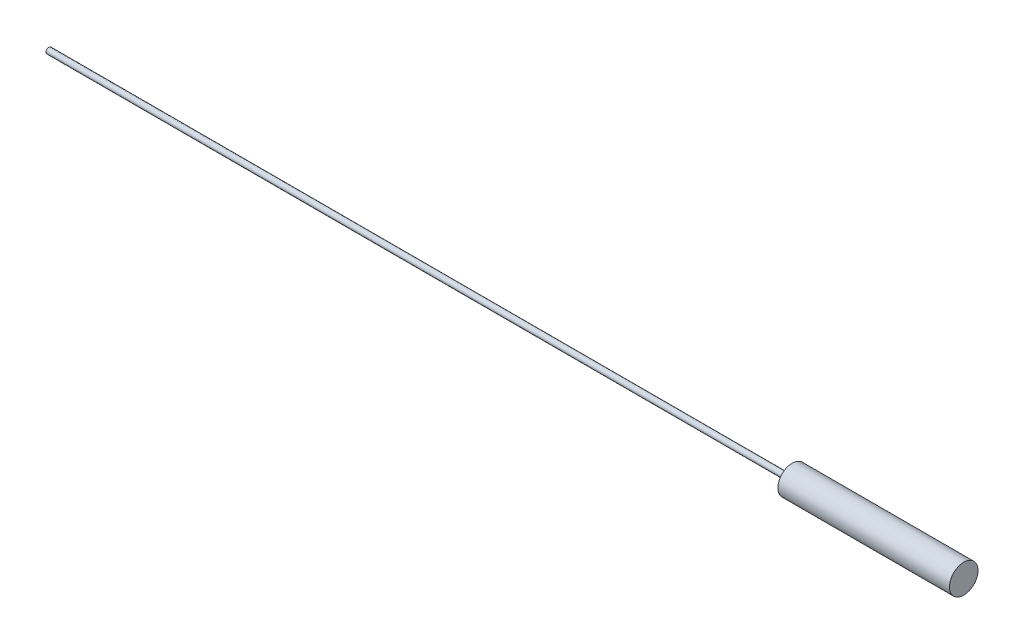
SolidWorks part; units mm, degrees
material "PVC 0.007 Plasticized"
ref_plane "Front" through (0, 0, 0) normal (0, 0, 1) x (1, 0, 0)
ref_plane "Top" through (0, 0, 0) normal (0, 1, 0) x (1, 0, 0)
ref_plane "Right" through (0, 0, 0) normal (1, 0, 0) x (0, 0, -1)
sketch "Sketch1" plane through (0, 0, 0) normal (0, 1, 0) x (1, 0, 0)
  line L0 (-60, 3.4256) -> (60, 3.4256)
  line L2 (-60, 3.4256) -> (60, 3.4256)
  line L3 (-60, 3.4256) -> (-60, -6.5744)
  line L4 (-60, -6.5744) -> (60, -6.5744)
  line L5 (60, 3.4256) -> (60, -6.5744)
  point P3 (0, 0)
  point P4 (0, 0)
  point P5 (61.3295, -0.348)
  point P6 (0, 0)
  dimension "D1" = 120
  dimension "D2" = 10
revolve "Revolve1" add sketch "Sketch1" angle 360 about L0
sketch "Sketch31" plane through (-60, 0, 0) normal (-1, 0, 0) x (0, 0, 1)
  line L0 (-13.4256, 0) -> (6.5744, 0) construction
  circle A0 centre (-3.4256, 0) radius 10 construction
  circle A1 centre (-3.4256, 0) radius 2
extrude "Boss-Extrude2" add sketch "Sketch31" along normal blind 520 contours A1
